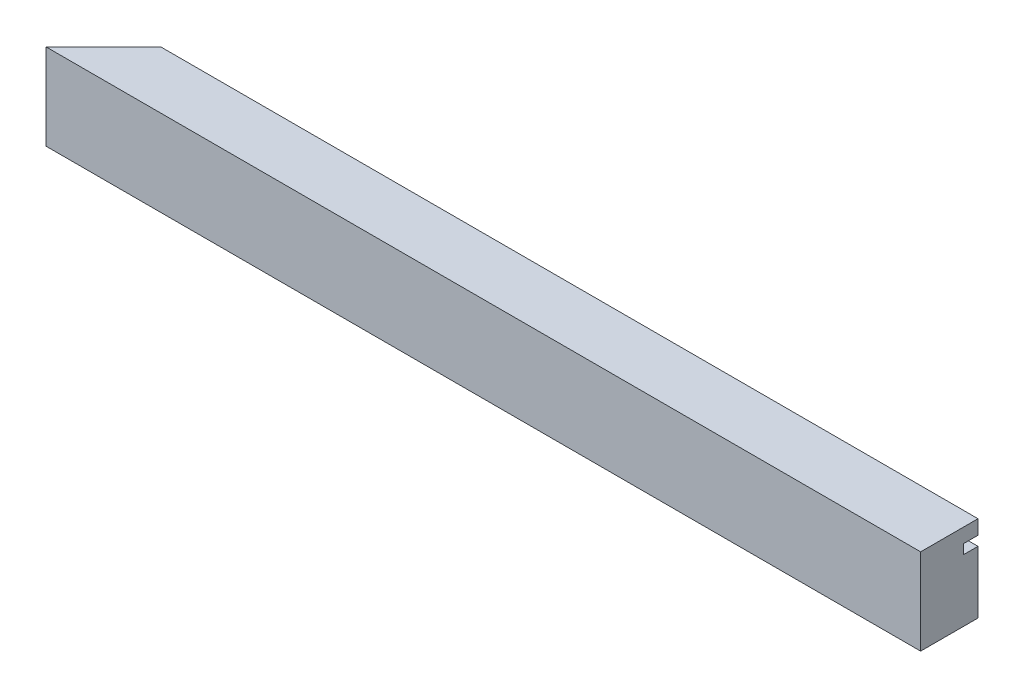
SolidWorks part; units mm, degrees
ref_plane "Front Plane" through (0, 0, 0) normal (0, 0, 1) x (1, 0, 0)
ref_plane "Top Plane" through (0, 0, 0) normal (0, 1, 0) x (1, 0, 0)
ref_plane "Right Plane" through (0, 0, 0) normal (1, 0, 0) x (0, 0, -1)
sketch "Sketch1" plane through (0, 0, 0) normal (0, 1, 0) x (1, 0, 0)
  line L0 (0, 0) -> (12, 12)
  line L1 (12, 12) -> (183, 12)
  line L2 (183, 12) -> (183, 0)
  line L3 (183, 0) -> (0, 0)
  line L4 (0, 0) -> (0, 0.7121)
  dimension "D1" = 171
  dimension "D2" = 12
  dimension "D3" = 45
  dimension "D4" = 183
extrude "Boss-Extrude1" add sketch "Sketch1" along normal blind 18 contours L3 L2 L1 L0
sketch "Sketch2" plane through (183, 0, 0) normal (1, 0, 0) x (0, 0, -1)
  line L1 (12, 13) -> (9, 13)
  line L2 (12, 15) -> (0, 15)
  line L3 (12, 15) -> (9, 15)
  line L5 (12, 13) -> (0, 13) construction
  line L6 (9, 18) -> (9, 0)
  line L7 (9, 15) -> (9, 13)
  line L8 (12, 15) -> (0, 15) construction
  dimension "D1" = 3
  dimension "D2" = 3
extrude "Cut-Extrude1" cut sketch "Sketch2" against normal through all and the other way through all
